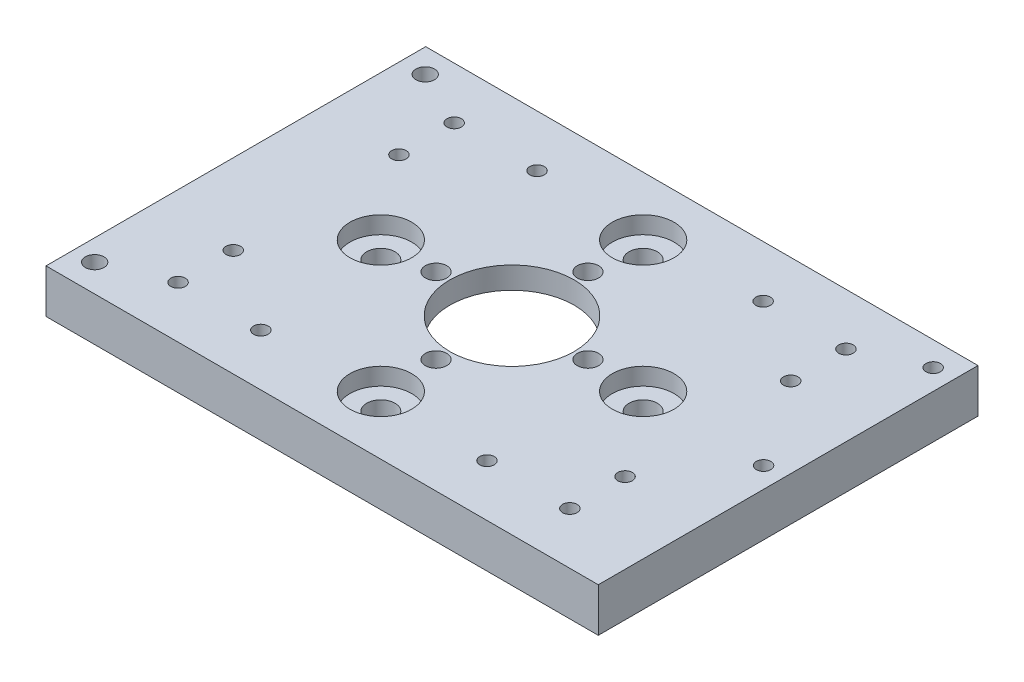
SolidWorks part; units mm, degrees
material "6061 Alloy"
ref_plane "Front Plane" through (0, 0, 0) normal (0, 0, 1) x (1, 0, 0)
ref_plane "Top Plane" through (0, 0, 0) normal (0, 1, 0) x (1, 0, 0)
ref_plane "Right Plane" through (0, 0, 0) normal (1, 0, 0) x (0, 0, -1)
sketch "Sketch1" plane through (0, 0, 0) normal (0, 1, 0) x (1, 0, 0)
  line L0 (-40, -27.5) -> (40, -27.5)
  line L1 (-40, -27.5) -> (-40, 27.5)
  line L2 (-40, 27.5) -> (40, 27.5)
  line L3 (40, -27.5) -> (40, 27.5)
  line L4 (-40, -27.5) -> (40, 27.5) construction
  line L5 (-40, 27.5) -> (40, -27.5) construction
  line L6 (0.0623, -0.303) -> (55.5765, -0.7148) construction
  line L7 (0, -187.7979) -> (0, 187.7979) construction
  line L10 (-3.4925, 0) -> (3.4925, 0) construction
  line L11 (0, -3.4925) -> (0, 3.4925) construction
  circle A23 centre (0, 0) radius 11 construction
  circle A24 centre (0, 11) radius 1.55
  circle A25 centre (11, 0) radius 1.55
  circle A26 centre (0, -11) radius 1.55
  circle A27 centre (-11, 0) radius 1.55
  circle A33 centre (0, 0) radius 19 construction
  circle A36 centre (0, 19) radius 2.05
  circle A37 centre (19, 0) radius 2.05
  circle A39 centre (0, -19) radius 2.05
  circle A42 centre (-19, 0) radius 2.05
  circle A53 centre (37.0175, 23.9874) radius 1.05
  circle A62 centre (-36.5553, 23.9874) radius 1.35
  circle A63 centre (-36.5553, 23.9874) radius 1.55 construction
  circle A64 centre (-36.9399, -23.5126) radius 1.35
  circle A65 centre (0, 0) radius 9
  circle A66 centre (-36.9399, -23.5126) radius 1.55 construction
  circle A67 centre (16.375, -20) radius 1.05
  circle A68 centre (28.375, -12) radius 1.05
  circle A69 centre (28.375, -20) radius 1.05
  circle A70 centre (28.375, 20) radius 1.05
  circle A71 centre (28.375, 12) radius 1.05
  circle A72 centre (16.375, 20) radius 1.05
  circle A73 centre (-28.375, -20) radius 1.05
  circle A74 centre (-28.375, -12) radius 1.05
  circle A76 centre (-16.375, -20) radius 1.05
  circle A77 centre (-16.375, 20) radius 1.05
  circle A78 centre (-28.375, 12) radius 1.05
  circle A79 centre (-28.375, 20) radius 1.05
  circle A80 centre (37.0175, -0.5771) radius 1.05
  point P0 (0, 0)
  point P65 (0, 0)
  point P66 (0, 0)
  point P76 (0, 0)
  dimension "D7" = 18
  dimension "D11" = 3.1
  dimension "D13" = 22
  dimension "4.2" = 4.1
  dimension "D14" = 38
  dimension "D3" = 2.7
  dimension "D8" = 2.7
  dimension "D4" = 2.1
  dimension "D5" = 2.1
  dimension "D6" = 2.1
  dimension "D9" = 2.1
  dimension "D10" = 2.1
  dimension "D1" = 80
  dimension "D2" = 55
  dimension "D12" = 4
  dimension "D16" = 4
extrude "Boss-Extrude1" add sketch "Sketch1" along normal blind 6.35
sketch "Sketch3" plane through (0, 6.35, 0) normal (0, 1, 0) x (1, 0, 0)
  circle A0 centre (0, 0) radius 19 construction
  circle A4 centre (0, -19) radius 4.47
  circle A6 centre (19, 0) radius 4.47
  circle A7 centre (-19, 0) radius 4.47
  circle A8 centre (0, 19) radius 4.47
  point P9 (0, 0)
  dimension "D1" = 8.94
  dimension "D2" = 4
extrude "Cut-Extrude2" cut sketch "Sketch3" against normal blind 2.5
sketch "Sketch2" plane through (0, 0, 0) normal (0, -1, 0) x (1, 0, 0)
  line L5 (-14.5, 14.5) -> (14.5, 14.5)
  line L6 (-14.5, 14.5) -> (-14.5, -14.5)
  line L7 (-14.5, -14.5) -> (14.5, -14.5)
  line L8 (14.5, 14.5) -> (14.5, -14.5)
  line L9 (-14.5, 14.5) -> (14.5, -14.5) construction
  line L10 (-14.5, -14.5) -> (14.5, 14.5) construction
  point P0 (0, 0)
  dimension "D1" = 29
  dimension "D2" = 29
extrude "Cut-Extrude1" cut sketch "Sketch2" against normal blind 3.175
fillet "Fillet1" radius 6.35 4 edges at (-14.5, 1.5875, -14.5) (-14.5, 1.5875, 14.5) (14.5, 1.5875, 14.5) (14.5, 1.5875, -14.5)
equation "\"D6@Sketch1\"=\"D4@Sketch1\""
equation "\"D5@Sketch1\"=\"D4@Sketch1\""
equation "\"D8@Sketch1\"=\"D3@Sketch1\""
